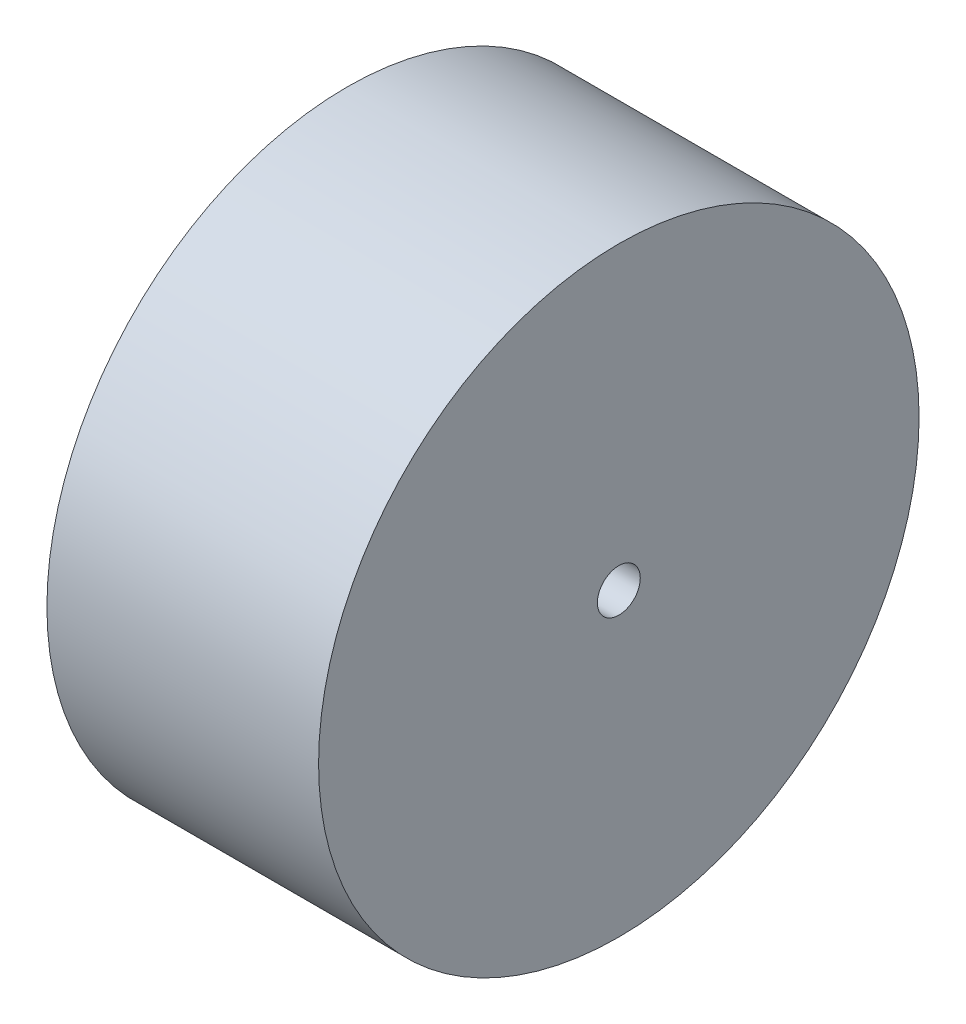
SolidWorks part; units mm, degrees
ref_plane "Front Plane" through (0, 0, 0) normal (0, 0, 1) x (1, 0, 0)
ref_plane "Top Plane" through (0, 0, 0) normal (0, 1, 0) x (1, 0, 0)
ref_plane "Right Plane" through (0, 0, 0) normal (1, 0, 0) x (0, 0, -1)
sketch "Sketch1" plane through (0, 0, 0) normal (1, 0, 0) x (0, 0, -1)
  circle A0 centre (0, 0) radius 21
  dimension "D1" = 42
extrude "Boss-Extrude1" add sketch "Sketch1" along normal blind 19
sketch "Sketch2" plane through (19, 0, 0) normal (1, 0, 0) x (0, 0, -1)
  circle A0 centre (0, 0) radius 1.5
  dimension "D1" = 3
extrude "Cut-Extrude1" cut sketch "Sketch2" against normal through all
